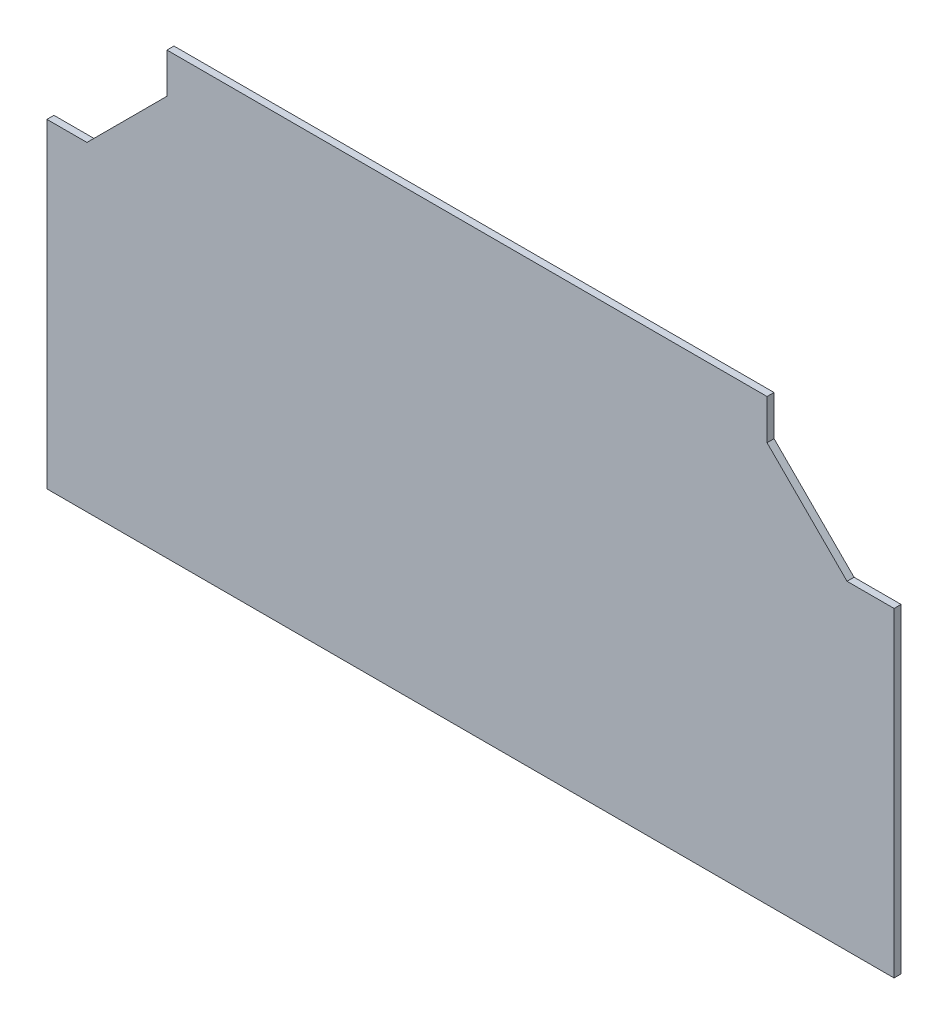
SolidWorks part; units mm, degrees
ref_plane "Front Plane" through (0, 0, 0) normal (0, 0, 1) x (1, 0, 0)
ref_plane "Top Plane" through (0, 0, 0) normal (0, 1, 0) x (1, 0, 0)
ref_plane "Right Plane" through (0, 0, 0) normal (1, 0, 0) x (0, 0, -1)
sketch "Sketch1" plane through (0, 0, 0) normal (0, 0, 1) x (1, 0, 0)
  line L0 (60, 0) -> (60, -20)
  line L1 (60, 0) -> (360, 0)
  line L2 (0, -60) -> (0, -220)
  line L3 (0, -220) -> (423.5, -220)
  line L4 (423.5, -60) -> (423.5, -220)
  line L7 (360, 0) -> (360, -20)
  line L10 (0, 0) -> (60, 0) construction
  line L11 (0, 0) -> (0, -60) construction
  line L12 (360, 0) -> (423.5, 0) construction
  line L13 (423.5, 0) -> (423.5, -60) construction
  line L14 (360, -20) -> (400, -60)
  line L15 (400, -60) -> (423.5, -60)
  line L16 (0, -60) -> (20, -60)
  line L17 (20, -60) -> (60, -20)
  dimension "D1" = 423.5
  dimension "D2" = 220
  dimension "D3" = 60
  dimension "D4" = 363.5
  dimension "D5" = 20
  dimension "D6" = 56.5685
  dimension "D7" = 20
  dimension "D8" = 300
  dimension "D9" = 60
  dimension "D10" = 56.5685
extrude "Boss-Extrude1" add sketch "Sketch1" along normal blind 3.5
